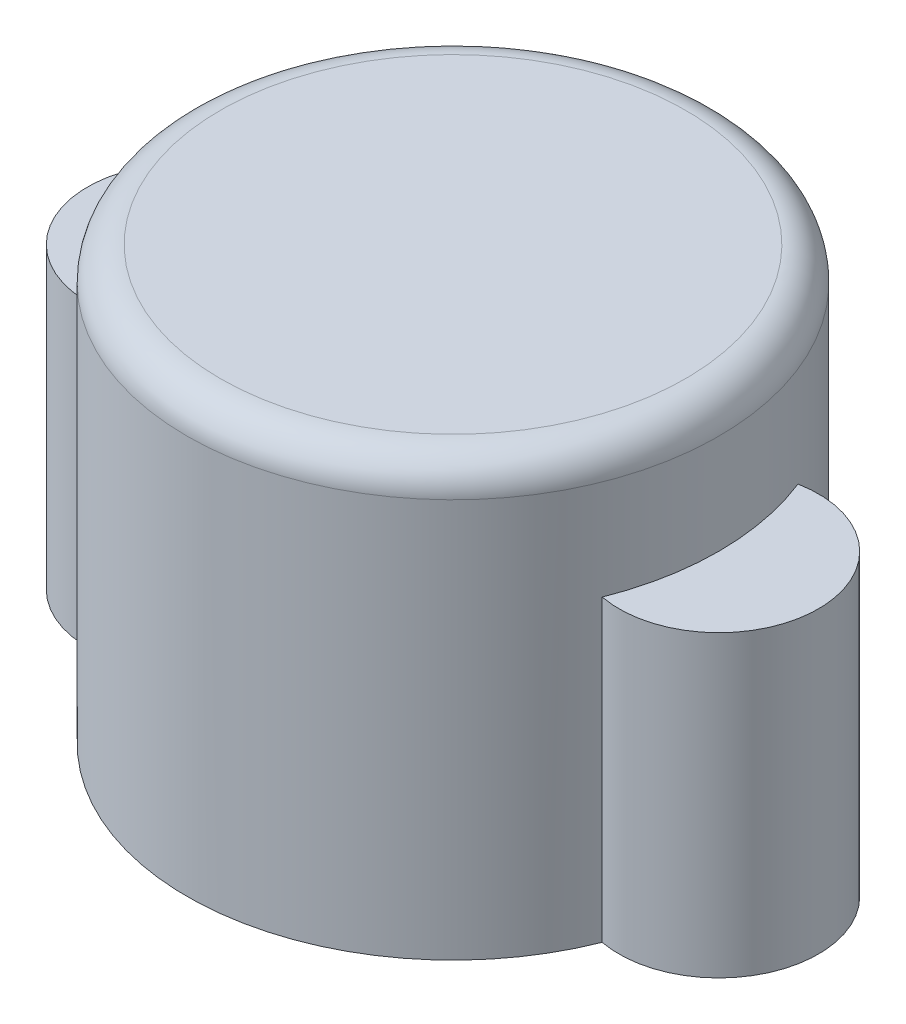
SolidWorks part; units mm, degrees
ref_plane "Front Plane" through (0, 0, 0) normal (0, 0, 1) x (1, 0, 0)
ref_plane "Top Plane" through (0, 0, 0) normal (0, 1, 0) x (1, 0, 0)
ref_plane "Right Plane" through (0, 0, 0) normal (1, 0, 0) x (0, 0, -1)
sketch "Sketch1" plane through (0, 0, 0) normal (0, 1, 0) x (1, 0, 0)
  line L0 (0, 0) -> (33.2163, 0) construction
  line L1 (0, 8) -> (0, -8) construction
  circle A0 centre (0, 0) radius 8
  circle A1 centre (8, 0) radius 3
  circle A2 centre (-8, 0) radius 3
  dimension "D1" = 16
  dimension "D2" = 6
  dimension "D3" = 8
extrude "Boss-Extrude1" add sketch "Sketch1" along normal blind 9 contours A2 A0 | A2 A0 | A0 A2 A1 | A0 A1 | A0 A1
sketch "Sketch2" plane through (0, 9, 0) normal (0, 1, 0) x (1, 0, 0)
  circle A0 centre (0, 0) radius 8
extrude "Boss-Extrude2" add sketch "Sketch2" along normal blind 4
fillet "Fillet1" radius 1 1 edges at (0, 13, 8)
